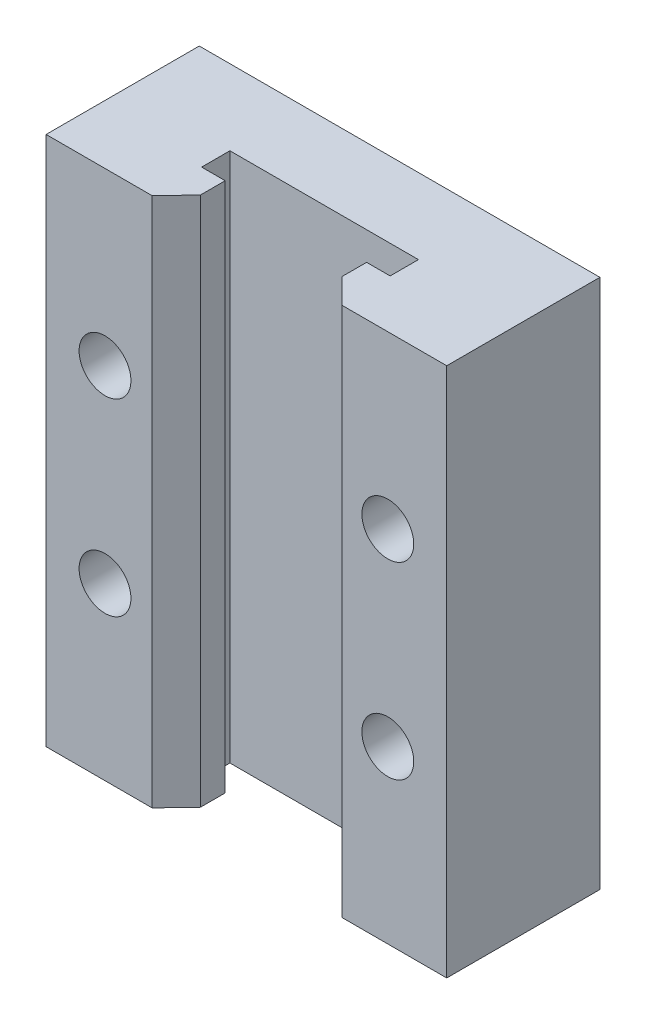
SolidWorks part; units mm, degrees
ref_plane "前视基准面" through (0, 0, 0) normal (0, 0, 1) x (1, 0, 0)
ref_plane "上视基准面" through (0, 0, 0) normal (0, 1, 0) x (1, 0, 0)
ref_plane "右视基准面" through (0, 0, 0) normal (1, 0, 0) x (0, 0, -1)
sketch "草图1" plane through (0, 0, 0) normal (0, 1, 0) x (1, 0, 0)
  line L0 (-4, 0.8249) -> (-3, 0.8249)
  line L1 (-3, 0.8249) -> (-3, -0.2251)
  line L2 (-4, -1.2751) -> (-8.5, -1.2751)
  line L3 (-8.5, -1.2751) -> (-8.5, 5.2249)
  line L4 (-8.5, 5.2249) -> (8.5, 5.2249)
  line L6 (4, 2.0249) -> (-4, 2.0249)
  line L7 (-4, 2.0249) -> (-4, 0.8249)
  line L8 (0, 5.2249) -> (0, -2.3974) construction
  line L9 (4, 2.0249) -> (4, 0.8249)
  line L10 (8.5, -1.2751) -> (8.5, 5.2249)
  line L11 (4.05, -1.2751) -> (8.5, -1.2751)
  line L12 (3, 0.8249) -> (3, -0.2251)
  line L13 (4, 0.8249) -> (3, 0.8249)
  line L14 (-3, -0.2251) -> (-4, -1.2751)
  line L15 (3, -0.2251) -> (4.05, -1.2751)
  point P12 (0, 2.0249)
  dimension "D1" = 6.5
  dimension "D2" = 17
  dimension "D3" = 4
  dimension "D4" = 1
  dimension "D5" = 3.2
  dimension "D7" = 1.2
extrude "凸台-拉伸1" add sketch "草图1" along normal blind 22.5
sketch "草图2" plane through (0, 0, -5.2249) normal (0, 0, -1) x (-1, 0, 0)
  line L0 (0, 22.5) -> (0, -6.1748) construction
  line L1 (-8.5, 22.5) -> (8.5, 22.5) construction
  line L2 (-8.5, 11.25) -> (19.4723, 11.25) construction
  line L3 (-8.5, 22.5) -> (-8.5, 0) construction
  circle A0 centre (-6, 15.25) radius 1.1
  circle A1 centre (6, 15.25) radius 1.1
  circle A2 centre (6, 7.25) radius 1.1
  circle A3 centre (-6, 7.25) radius 1.1
  dimension "D1" = 2.2
  dimension "D2" = 12
  dimension "D3" = 8
extrude "切除-拉伸1" cut sketch "草图2" against normal blind 10
